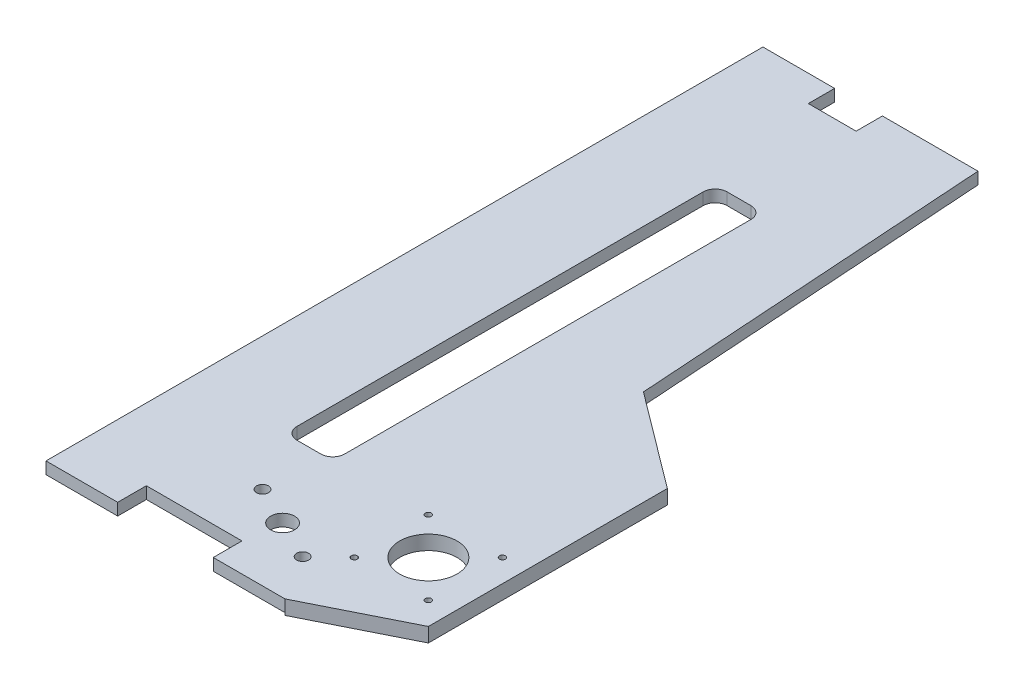
SolidWorks part; units mm, degrees
ref_plane "Front Plane" through (0, 0, 0) normal (0, 0, 1) x (1, 0, 0)
ref_plane "Top Plane" through (0, 0, 0) normal (0, 1, 0) x (1, 0, 0)
ref_plane "Right Plane" through (0, 0, 0) normal (1, 0, 0) x (0, 0, -1)
sketch "Sketch1" plane through (0, 0, 0) normal (0, 1, 0) x (1, 0, 0)
  line L0 (0, 0) -> (30, 0)
  line L1 (30, 0) -> (30, 12)
  line L2 (30, 12) -> (70, 12)
  line L3 (70, 12) -> (70, 0)
  line L4 (70, 0) -> (100, 0)
  line L5 (0, 0) -> (0, 300)
  line L6 (0, 300) -> (100, 300)
  line L7 (100, 300) -> (100, 0)
  dimension "D1" = 30
  dimension "D2" = 12
  dimension "D3" = 40
  dimension "D4" = 12
  dimension "D5" = 30
  dimension "D6" = 300
extrude "Boss-Extrude1" add sketch "Sketch1" along normal blind 5
sketch "Sketch2" plane through (0, 5, 0) normal (0, 1, 0) x (1, 0, 0)
  line L0 (50, 12) -> (50, 27) construction
  line L1 (30, 12) -> (70, 12) construction
  line L2 (50, 27) -> (72, 27) construction
  line L3 (72, 27) -> (88.4031, 19) construction
  line L4 (88.4031, 19) -> (88.4031, 27) construction
  line L5 (88.4031, 27) -> (72, 27) construction
  line L6 (88.4031, 19) -> (55.5969, 35) construction
  circle A0 centre (72, 27) radius 5
  circle A1 centre (88.4031, 19) radius 2.5
  circle A2 centre (55.5969, 35) radius 2.5
  point P13 (72.8461, 28.7348)
  dimension "D3" = 10
  dimension "D5" = 5
  dimension "D1" = 15
  dimension "D2" = 22
  dimension "D4" = 18.25
  dimension "D7" = 8
  dimension "D8" = 36.5
  dimension "D6" = 2
extrude "Cut-Extrude1" cut sketch "Sketch2" against normal blind 6
sketch "Sketch4" plane through (0, 5, 0) normal (0, 1, 0) x (1, 0, 0)
  line L0 (100, 300) -> (0, 300) construction
  line L1 (50, 300) -> (30, 300)
  line L2 (50, 300) -> (50, 289)
  line L3 (50, 289) -> (30, 289)
  line L4 (30, 300) -> (30, 289)
  dimension "D1" = 11
  dimension "D2" = 20
extrude "Cut-Extrude3" cut sketch "Sketch4" against normal blind 10
sketch "Sketch6" plane through (0, 5, 0) normal (0, 1, 0) x (1, 0, 0)
  line L0 (100, 0) -> (100, 150)
  line L1 (100, 150) -> (140, 120)
  line L2 (140, 120) -> (140, 20)
  line L3 (140, 20) -> (100, 0)
  dimension "D1" = 150
  dimension "D2" = 100
  dimension "D3" = 40
  dimension "D4" = 20
extrude "Boss-Extrude3" add sketch "Sketch6" against normal blind 6
sketch "Sketch7" plane through (0, 5, 0) normal (0, 1, 0) x (1, 0, 0)
  line L0 (100, 0) -> (100, 45) construction
  line L1 (100, 45) -> (115, 45) construction
  line L3 (99.5, 60.5) -> (130.5, 60.5) construction
  line L4 (99.5, 60.5) -> (99.5, 29.5) construction
  line L5 (99.5, 29.5) -> (130.5, 29.5) construction
  line L6 (130.5, 60.5) -> (130.5, 29.5) construction
  line L7 (99.5, 60.5) -> (130.5, 29.5) construction
  line L8 (99.5, 29.5) -> (130.5, 60.5) construction
  circle A0 centre (130.5, 60.5) radius 1.25
  circle A4 centre (99.5, 60.5) radius 1.25
  circle A5 centre (99.5, 29.5) radius 1.25
  circle A6 centre (130.5, 29.5) radius 1.25
  circle A7 centre (115, 45) radius 12
  point P18 (110, 100)
  dimension "D4" = 2.5
  dimension "D5" = 2.5
  dimension "D6" = 2.5
  dimension "D7" = 2.5
  dimension "D8" = 24
  dimension "D1" = 45
  dimension "D2" = 15
  dimension "D3" = 31
extrude "Cut-Extrude4" cut sketch "Sketch7" against normal blind 6
sketch "Sketch9" plane through (0, 5, 0) normal (0, 1, 0) x (1, 0, 0)
  line L0 (100, 300) -> (90, 300)
  line L1 (100, 300) -> (50, 300) construction
  line L2 (90, 300) -> (100, 150)
  line L3 (100, 150) -> (100, 300)
  line L4 (0, 150) -> (50, 150) construction
  line L5 (0, 300) -> (0, 0) construction
  line L7 (40, 240) -> (60, 240)
  line L8 (40, 240) -> (40, 60)
  line L9 (40, 60) -> (60, 60)
  line L10 (60, 240) -> (60, 60)
  line L11 (40, 240) -> (60, 60) construction
  line L12 (40, 60) -> (60, 240) construction
  dimension "D1" = 10
  dimension "D2" = 50
  dimension "D3" = 180
  dimension "D4" = 20
extrude "Cut-Extrude5" cut sketch "Sketch9" against normal blind 6
fillet "Fillet1" radius 5 4 edges at (40, 2.5, -240) (60, 2.5, -240) (60, 2.5, -60) (40, 2.5, -60)
